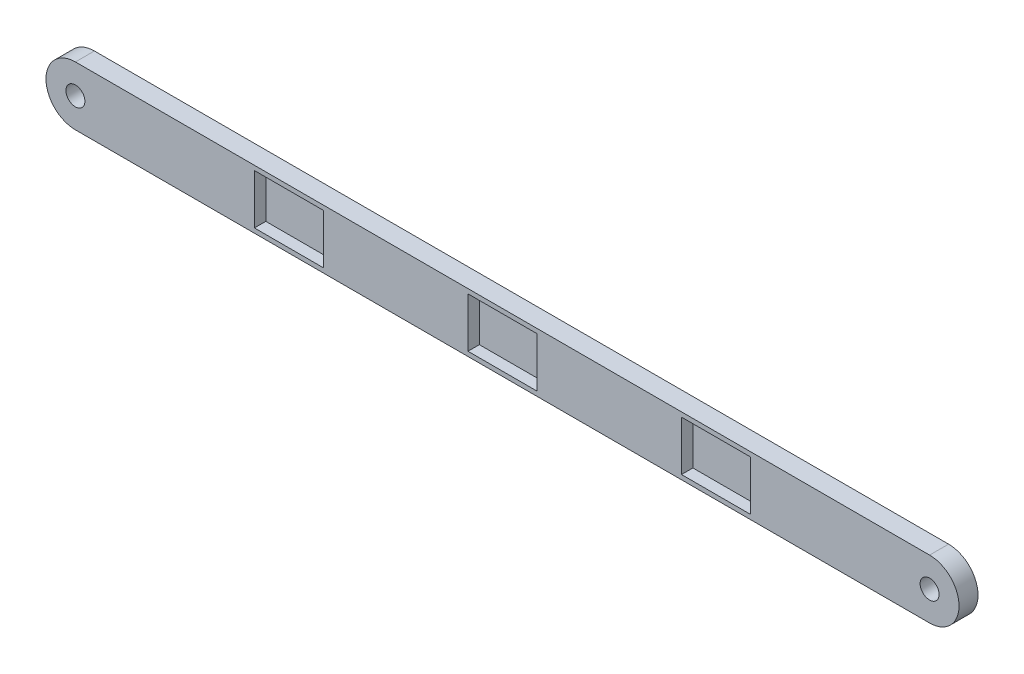
SolidWorks part; units mm, degrees
ref_plane "Alzado" through (0, 0, 0) normal (0, 0, 1) x (1, 0, 0)
ref_plane "Planta" through (0, 0, 0) normal (0, 1, 0) x (1, 0, 0)
ref_plane "Vista lateral" through (0, 0, 0) normal (1, 0, 0) x (0, 0, -1)
sketch "Croquis1" plane through (0, 0, 0) normal (0, 0, 1) x (1, 0, 0)
  line L3 (-112.5, 7.75) -> (112.5, 7.75)
  line L4 (-112.5, -7.75) -> (112.5, -7.75)
  circle A2 centre (112.5, 0) radius 2.5
  circle A3 centre (-112.5, 0) radius 2.5
  arc A5 (-112.5, 7.75) -> (-112.5, -7.75) centre (-112.5, 0) ccw
  arc A6 (112.5, -7.75) -> (112.5, 7.75) centre (112.5, 0) ccw
  dimension "D3" = 5
  dimension "D4" = 5
  dimension "D7" = 225
  dimension "D8" = 225
extrude "Saliente-Extruir1" add sketch "Croquis1" along normal mid plane 5
sketch "Croquis4" plane through (0, 0, 2.5) normal (0, 0, 1) x (1, 0, 0)
  line L0 (-112.5, 0) -> (0, 0) construction
  line L1 (-9.1, 6.55) -> (9.1, 6.55)
  line L2 (-112.5, -7.75) -> (112.5, -7.75)
  line L3 (112.5, 7.75) -> (-112.5, 7.75)
  line L4 (-112.5, -7.75) -> (112.5, -7.75)
  line L5 (112.5, 7.75) -> (-112.5, 7.75)
  line L6 (-9.1, 6.55) -> (-9.1, -6.55)
  line L7 (-9.1, -6.55) -> (9.1, -6.55)
  line L8 (9.1, 6.55) -> (9.1, -6.55)
  line L9 (-9.1, 6.55) -> (9.1, -6.55) construction
  line L10 (-9.1, -6.55) -> (9.1, 6.55) construction
  line L11 (0, 0) -> (112.5, 0) construction
  line L13 (-65.35, 6.55) -> (-47.15, 6.55)
  line L14 (-65.35, 6.55) -> (-65.35, -6.55)
  line L15 (-65.35, -6.55) -> (-47.15, -6.55)
  line L16 (-47.15, 6.55) -> (-47.15, -6.55)
  line L17 (-65.35, 6.55) -> (-47.15, -6.55) construction
  line L18 (-65.35, -6.55) -> (-47.15, 6.55) construction
  line L19 (47.15, 6.55) -> (65.35, 6.55)
  line L20 (47.15, 6.55) -> (47.15, -6.55)
  line L21 (47.15, -6.55) -> (65.35, -6.55)
  line L22 (65.35, 6.55) -> (65.35, -6.55)
  line L23 (47.15, 6.55) -> (65.35, -6.55) construction
  line L24 (47.15, -6.55) -> (65.35, 6.55) construction
  arc A2 (-112.5, 7.75) -> (-112.5, -7.75) centre (-112.5, 0) ccw
  arc A3 (112.5, -7.75) -> (112.5, 7.75) centre (112.5, 0) ccw
  arc A4 (-112.5, 7.75) -> (-112.5, -7.75) centre (-112.5, 0) ccw
  arc A5 (112.5, -7.75) -> (112.5, 7.75) centre (112.5, 0) ccw
  point P0 (0, 0)
  point P12 (-56.25, 0)
  point P18 (56.25, 0)
  dimension "D2" = 13.1
  dimension "D3" = 18.2
  dimension "D4" = 18.2
  dimension "D5" = 13.1
  dimension "D6" = 13.1
  dimension "D7" = 18.2
  dimension "D1" = 0
extrude "Cortar-Extruir4" cut sketch "Croquis4" against normal blind 3 contours L13 L16 L15 L14 | L6 L1 L8 L7 | L20 L19 L22 L21
